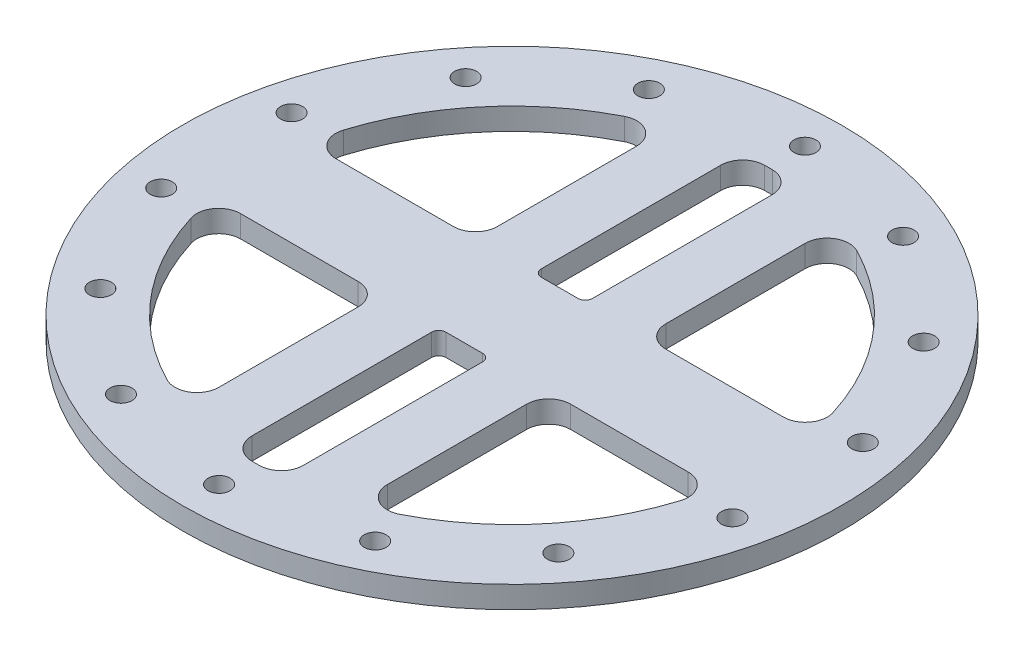
SolidWorks part; units mm, degrees
ref_plane "Спереди" through (0, 0, 0) normal (0, 0, 1) x (1, 0, 0)
ref_plane "Сверху" through (0, 0, 0) normal (0, 1, 0) x (1, 0, 0)
ref_plane "Справа" through (0, 0, 0) normal (1, 0, 0) x (0, 0, -1)
other "Configuration Table"
sketch "Эскиз1" plane through (0, 0, 0) normal (0, 1, 0) x (1, 0, 0)
  circle A0 centre (0, 0) radius 45
  circle A1 centre (0, 0) radius 35
  dimension "D1" = 90
  dimension "D2" = 70
extrude "Бобышка-Вытянуть1" add sketch "Эскиз1" along normal blind 3
sketch "Эскиз2" plane through (0, 0, 0) normal (0, 1, 0) x (1, 0, 0)
  line L0 (-1000, 0) -> (49000, 0) construction
  line L1 (-34.3911, 6.5) -> (34.3911, 6.5)
  line L2 (-34.3911, -6.5) -> (34.3911, -6.5)
  circle A0 centre (0, 0) radius 35 construction
  circle A1 centre (0, 0) radius 35
  dimension "D1" = 13
  dimension "D2" = 6.5
extrude "Бобышка-Вытянуть2" add sketch "Эскиз2" along normal blind 3 contours A1 L0 L1 | L0 A1 L2
sketch "Эскиз3" plane through (0, 3, 0) normal (0, 1, 0) x (1, 0, 0)
  line L0 (0, -1000) -> (0, 49000) construction
  circle A0 centre (0, 0) radius 40 construction
  circle A2 centre (0, 40) radius 1.5
  dimension "D1" = 80
  dimension "D2" = 3
extrude "Вырез-Вытянуть1" cut sketch "Эскиз3" against normal blind 3
pattern_circular "Круговой массив1" count 14 over 360 about axis through (0, 0, 0) along (0, 1, 0) of "Вырез-Вытянуть1"
fillet "Скругление1" radius 3 4 edges at (-34.3911, 1.5, -6.5) (34.3911, 1.5, -6.5) (34.3911, 1.5, 6.5) (-34.3911, 1.5, 6.5)
sketch "Эскиз4" plane through (0, 0, 0) normal (0, 1, 0) x (1, 0, 0)
  line L0 (0, -1000) -> (0, 49000) construction
  line L1 (-3.5, 6.5) -> (-3.5, 34.8246)
  line L2 (-30.5573, 6.5) -> (30.5573, 6.5) construction
  line L3 (3.5, 6.5) -> (3.5, 34.8246)
  line L4 (-11.5, 33.0568) -> (-11.5, 6.5)
  line L5 (-11.5, 6.5) -> (-3.5, 6.5)
  line L6 (11.5, 6.5) -> (11.5, 33.0568)
  line L7 (3.5, 6.5) -> (11.5, 6.5)
  arc A0 (33.4221, 10.3906) -> (-33.4221, 10.3906) centre (0, 0) ccw construction
  arc A1 (11.5, 33.0568) -> (3.5, 34.8246) centre (0, 0) ccw
  arc A2 (-3.5, 34.8246) -> (-11.5, 33.0568) centre (0, 0) ccw
  dimension "D1" = 7
  dimension "D2" = 3.5
  dimension "D3" = 8
  dimension "D4" = 8
extrude "Бобышка-Вытянуть3" add sketch "Эскиз4" along normal blind 3
fillet "Скругление2" radius 3 6 edges at (3.5, 1.5, -34.8246) (-3.5, 1.5, -34.8246) (-11.5, 1.5, -6.5) (-11.5, 1.5, -33.0568) (11.5, 1.5, -6.5) (11.5, 1.5, -33.0568)
mirror "Зеркальное отражение1" about plane through (0, 0, 0) normal (0, 0, 1) of "Бобышка-Вытянуть3"
fillet "Скругление3" radius 1 4 edges at (-3.5, 1.5, 6.5) (3.5, 1.5, 6.5) (-3.5, 1.5, -6.5) (3.5, 1.5, -6.5)
fillet "Скругление4" radius 3 6 edges at (-11.5, 1.5, 33.0568) (-11.5, 1.5, 6.5) (11.5, 1.5, 33.0568) (11.5, 1.5, 6.5) (-3.5, 1.5, 34.8246) (3.5, 1.5, 34.8246)
